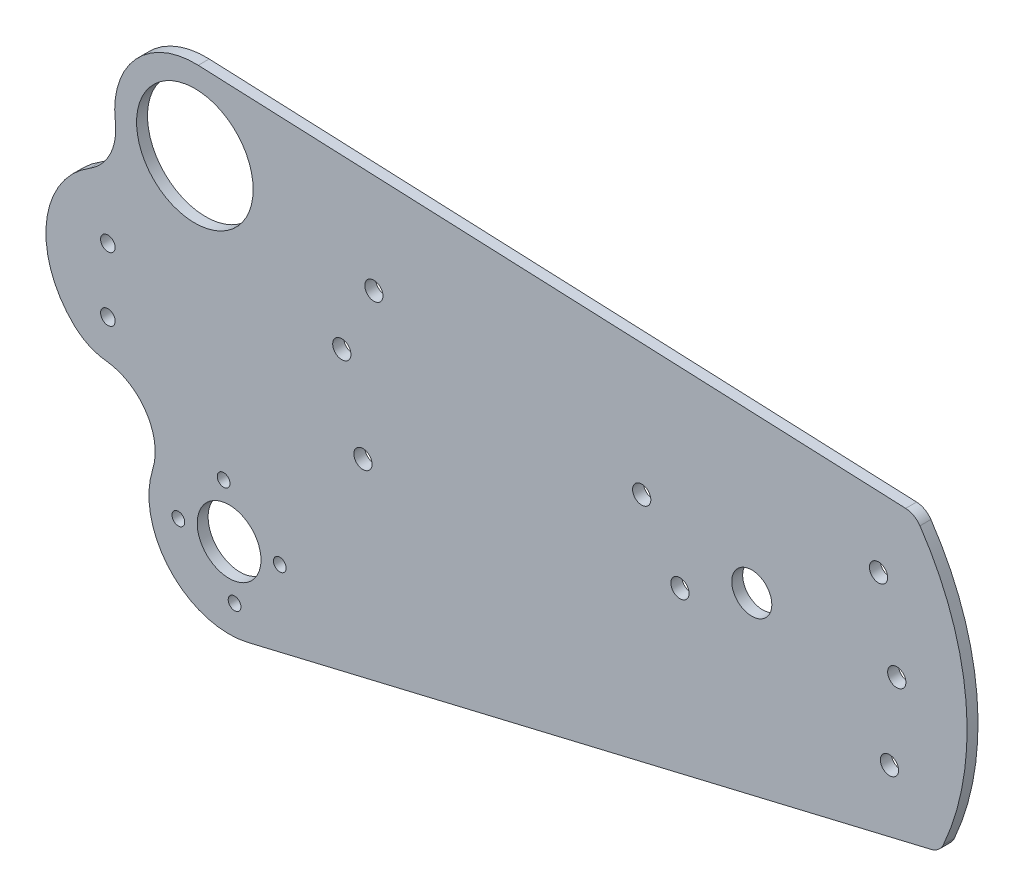
SolidWorks part; units mm, degrees
ref_plane "Front Plane" through (0, 0, 0) normal (0, 0, 1) x (1, 0, 0)
ref_plane "Top Plane" through (0, 0, 0) normal (0, 1, 0) x (1, 0, 0)
ref_plane "Right Plane" through (0, 0, 0) normal (1, 0, 0) x (0, 0, -1)
sketch "Sketch1" plane through (0, 0, 0) normal (0, 0, 1) x (1, 0, 0)
  line L0 (85.276, -33.5) -> (-137.2004, -33.5) construction
  line L1 (-113.4953, 49.4802) -> (80.6428, 41.2477)
  line L2 (-116.8162, 49.6211) -> (-102.6443, -81.6153) construction
  line L3 (-99.4301, -80.7688) -> (92.3569, -30.258) construction
  line L4 (77.1884, 41.3942) -> (85.1314, -32.1609) construction
  line L5 (-109.7303, -15.9971) -> (81.1599, 4.6166) construction
  line L6 (91, -33.5) -> (-88.5, -33.5) construction
  line L7 (-97.4673, 5.5) -> (-155.3054, 5.5) construction
  line L8 (-138.3, -14) -> (-155.3054, -14) construction
  line L9 (-138.3, 5.5) -> (-138.3, -33.5) construction
  line L10 (-155.3054, 5.5) -> (-155.3054, -33.5) construction
  line L11 (38.4085, 33.5) -> (38.4085, -33.5) construction
  line L12 (-111.9277, -83.7457) -> (87.5904, -36.3264)
  line L13 (-91.5, 33.5) -> (88, 33.5) construction
  line L14 (-68.3, -21.5) -> (-108.6653, -25.8589) construction
  circle A0 centre (38.4085, 0) radius 5.5
  circle A1 centre (-114.4274, 27.5) radius 14 construction
  circle A2 centre (-105.0331, -59.4942) radius 14 construction
  arc A3 (-91.5, 33.5) -> (-88.5, -33.5) centre (-18.0922, 3.2198) ccw construction
  circle A4 centre (-68.3, -21.5) radius 2.5
  circle A5 centre (-68.3, -21.5) radius 2.5 construction
  circle A6 centre (-138.3, -5.25) radius 2
  circle A7 centre (-138.3, -22.75) radius 2
  arc A8 (-143.3264, 10.0842) -> (-147.5429, -29.3643) centre (-130.3054, -11.2571) ccw
  arc A9 (-147.5429, -29.3643) -> (-137.2004, -33.5) centre (-137.2004, -18.5) ccw
  circle A10 centre (-114.4274, 27.5) radius 22
  arc A11 (87.5904, -36.3264) -> (91, -33.5) centre (86.4343, -31.4619) ccw
  circle A12 centre (-105.0331, -59.4942) radius 22
  arc A13 (91, -33.5) -> (84.5669, 39.0618) centre (22.6589, -2.9929) ccw
  arc A14 (91, -33.5) -> (88, 33.5) centre (22.6589, -2.9929) ccw construction
  arc A15 (84.5669, 39.0618) -> (80.6428, 41.2477) centre (80.4309, 36.2522) ccw
  arc A17 (-126.0093, -52.861) -> (-138.7558, -33.4191) centre (-140.3112, -48.3383) ccw
  arc A18 (-143.3264, 10.0842) -> (-136.2559, 24.7583) centre (-151.139, 22.889) ccw
  circle A19 centre (-74.1, 1.7) radius 2.5
  circle A20 centre (-65.3, 20) radius 2.5
  circle A21 centre (8.2, 8.3) radius 2.5
  circle A23 centre (18.7, -8.7) radius 2.5
  circle A25 centre (78.2, -0.1) radius 2.5
  circle A26 centre (76.2, -22) radius 2.5
  circle A27 centre (73.2, 22.3) radius 2.5
  circle A28 centre (73.2, 22.3) radius 2.5 construction
  circle A29 centre (78.2, -0.1) radius 2.5 construction
  circle A31 centre (8.2, 8.3) radius 2.5 construction
  circle A32 centre (18.7, -8.7) radius 2.5 construction
  circle A33 centre (76.2, -22) radius 2.5 construction
  circle A34 centre (-74.1, 1.7) radius 2.5 construction
  circle A35 centre (-65.3, 20) radius 2.5 construction
  circle A36 centre (-115.9305, 41.4191) radius 1.75
  circle A37 centre (-100.5083, 29.0031) radius 1.75
  circle A38 centre (-112.9243, 13.5809) radius 1.75
  circle A39 centre (-128.3465, 25.9969) radius 1.75
  circle A40 centre (-106.5362, -45.5752) radius 1.75
  circle A41 centre (-91.1141, -57.9912) radius 1.75
  circle A42 centre (-103.5301, -73.4133) radius 1.75
  circle A43 centre (-118.9522, -60.9973) radius 1.75
  circle A44 centre (38.4085, 0) radius 35 construction
  circle A45 centre (38.4085, 0) radius 43
  circle A49 centre (-105.0331, -59.4942) radius 16
  circle A50 centre (-114.4274, 27.5) radius 16
  circle A51 centre (-114.4274, 27.5) radius 8.75
  circle A52 centre (-105.0331, -59.4942) radius 8.75
  arc A53 (91, -33.5) -> (88, 33.5) centre (22.6589, -2.9929) ccw construction
  point P52 (81.1599, 4.6166)
  point P109 (-114.4274, 27.5)
  point P118 (-105.0331, -59.4942)
  dimension "D5" = 4
  dimension "D6" = 25
  dimension "D9" = 15
  dimension "D13" = 10
  dimension "D14" = 28
  dimension "D11" = 44
  dimension "D15" = 3.5
  dimension "D12" = 70
  dimension "D19" = 11
  dimension "D20" = 17.5
  dimension "D22" = 32
  dimension "D2" = 39
  dimension "D3" = 70
  dimension "D4" = 17.5
  dimension "D7" = 14
  dimension "D8" = 10
  dimension "D10" = 87.5
  dimension "D21" = 192
  dimension "D23" = 40.6
  dimension "D18" = 8
  dimension "D16" = 4
  dimension "D17" = 4
extrude "Boss-Extrude1" add sketch "Sketch1" along normal blind 3
